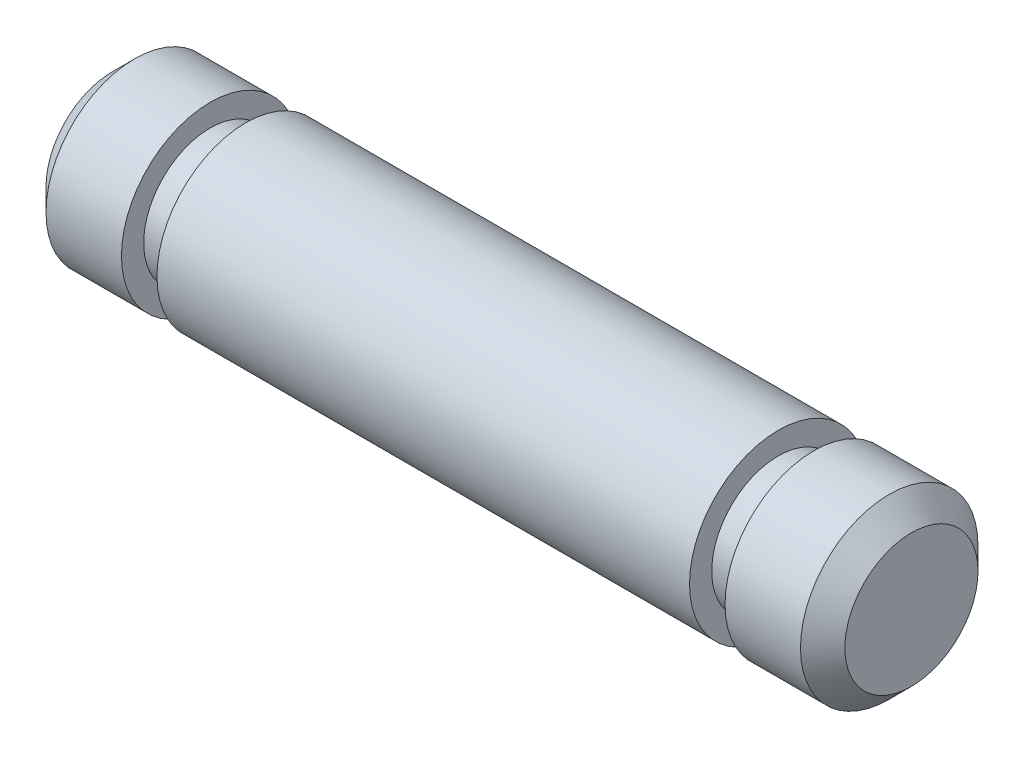
SolidWorks part; units mm, degrees
material "Cast Alloy Steel"
ref_plane "Front Plane" through (0, 0, 0) normal (0, 0, 1) x (1, 0, 0)
ref_plane "Top Plane" through (0, 0, 0) normal (0, 1, 0) x (1, 0, 0)
ref_plane "Right Plane" through (0, 0, 0) normal (1, 0, 0) x (0, 0, -1)
sketch "Sketch1" plane through (0, 0, 0) normal (1, 0, 0) x (0, 0, -1)
  circle A0 centre (0, 0) radius 2
  dimension "D1" = 4
extrude "Boss-Extrude1" add sketch "Sketch1" along normal mid plane 12
sketch "Sketch2" plane through (6, 0, 0) normal (1, 0, 0) x (0, 0, -1)
  circle A0 centre (0, 0) radius 1.5
  dimension "D1" = 3
extrude "Boss-Extrude2" add sketch "Sketch2" along normal blind 0.8
sketch "Sketch3" plane through (6.8, 0, 0) normal (1, 0, 0) x (0, 0, -1)
  circle A0 centre (0, 0) radius 2
  dimension "D1" = 4
extrude "Boss-Extrude3" add sketch "Sketch3" along normal blind 2.2
mirror "Mirror1" about plane through (0, 0, 0) normal (1, 0, 0) of "Boss-Extrude3", "Boss-Extrude2"
chamfer "Chamfer1" distance 0.5 angle 45 2 edges at (-9, 0, -2) (9, 0, -2)
